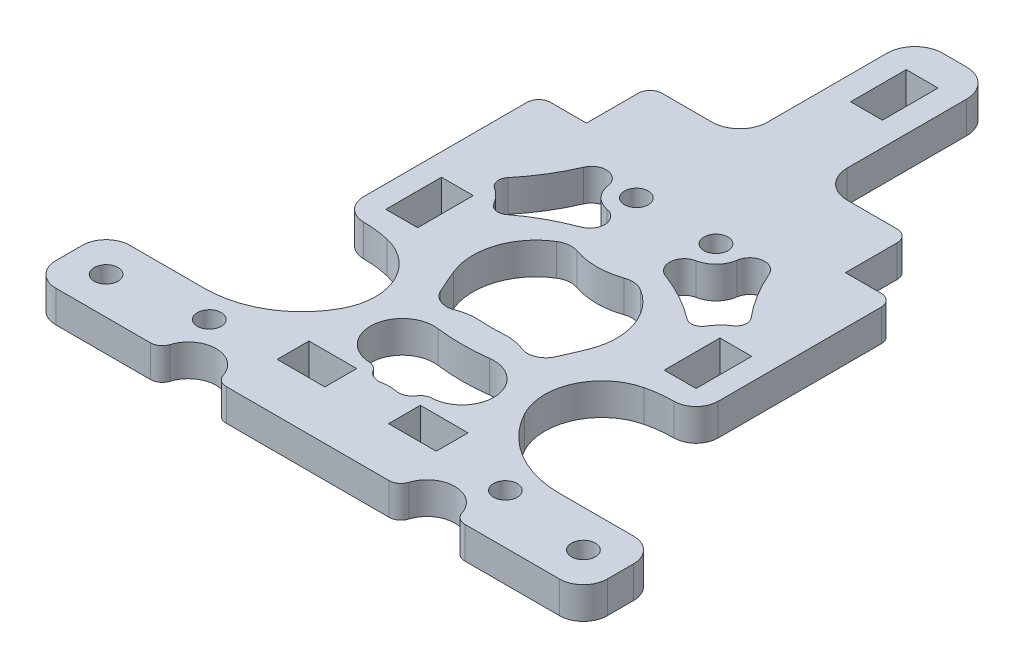
SolidWorks part; units mm, degrees
ref_plane "Plan de face" through (0, 0, 0) normal (0, 0, 1) x (1, 0, 0)
ref_plane "Plan de dessus" through (0, 0, 0) normal (0, 1, 0) x (1, 0, 0)
ref_plane "Plan de droite" through (0, 0, 0) normal (1, 0, 0) x (0, 0, -1)
sketch "Esquisse1" plane through (0, 0, 0) normal (0, 1, 0) x (1, 0, 0)
  line L0 (0, -203.16) -> (0, 154.3311) construction
  line L1 (-20.28, 5) -> (-22.28, 5)
  line L2 (-20.28, 5) -> (-16.28, 5)
  line L3 (-5, 35) -> (-5, 13)
  line L4 (-22.28, 5) -> (-22.28, -122.6773) construction
  line L5 (-22.28, -122.6773) -> (0.6971, -122.6773) construction
  line L6 (2, 30.92) -> (-2, 30.92)
  line L7 (-2, 30.92) -> (-2, 23.92)
  line L8 (-2, 23.92) -> (2, 23.92)
  line L9 (-18.1387, -5) -> (23.5208, -5) construction
  line L10 (-19.5, -10) -> (-15.5, -10)
  line L11 (-19.5, -10) -> (-19.5, -17)
  line L12 (-19.5, -17) -> (-15.5, -17)
  line L13 (-15.5, -10) -> (-15.5, -17)
  line L14 (-10, -36.16) -> (-4, -36.16)
  line L15 (-10, -36.16) -> (-10, -40.16)
  line L16 (-10, -40.16) -> (-4, -40.16)
  line L17 (-4, -36.16) -> (-4, -40.16)
  line L18 (-5, 35) -> (5, 35)
  line L19 (-22.28, 5) -> (-22.28, -37)
  line L21 (-5, 13) -> (-16.28, 13)
  line L22 (-16.28, 13) -> (-16.28, 5)
  line L23 (18.1387, -5) -> (-23.5208, -5) construction
  line L24 (16.28, 13) -> (16.28, 5)
  line L25 (5, 13) -> (16.28, 13)
  line L26 (22.28, 5) -> (22.28, -37)
  line L27 (4, -36.16) -> (4, -40.16)
  line L28 (10, -40.16) -> (4, -40.16)
  line L29 (10, -36.16) -> (10, -40.16)
  line L30 (10, -36.16) -> (4, -36.16)
  line L31 (15.5, -10) -> (15.5, -17)
  line L32 (19.5, -17) -> (15.5, -17)
  line L33 (19.5, -10) -> (19.5, -17)
  line L34 (19.5, -10) -> (15.5, -10)
  line L35 (2, 30.92) -> (2, 23.92)
  line L36 (5, 35) -> (5, 13)
  line L37 (20.28, 5) -> (16.28, 5)
  line L38 (20.28, 5) -> (22.28, 5)
  line L39 (-22.28, -37) -> (-34.66, -37)
  line L40 (-34.66, -37) -> (-34.66, -46.32)
  line L44 (-34.66, -46.32) -> (34.66, -46.32)
  line L45 (-30, -41.66) -> (-34.66, -37) construction
  line L46 (-30, -41.66) -> (-34.66, -46.32) construction
  line L47 (22.28, -37) -> (34.66, -37)
  line L48 (34.66, -37) -> (34.66, -46.32)
  line L49 (30, -41.66) -> (34.66, -37) construction
  line L50 (30, -41.66) -> (34.66, -46.32) construction
  circle A0 centre (-5, 0) radius 1.5
  circle A1 centre (5, 0) radius 1.5
  circle A2 centre (-30, -41.66) radius 1.5
  circle A3 centre (30, -41.66) radius 1.5
  point P38 (0, -40.4225)
  point P40 (0, 35)
  point P49 (0, 23.92)
  point P50 (0, 30.92)
  point P60 (0, -46.32)
  dimension "D2" = 3
  dimension "D22" = 3
  dimension "D1" = 10
  dimension "D3" = 15.28
  dimension "D4" = 4
  dimension "D5" = 5
  dimension "D6" = 6
  dimension "D7" = 7
  dimension "D8" = 2
  dimension "D9" = 26.16
  dimension "D10" = 4
  dimension "D11" = 8
  dimension "D12" = 13.5
  dimension "D13" = 40.92
  dimension "D14" = 5
  dimension "D15" = 40
  dimension "D16" = 6
  dimension "D17" = 5
  dimension "D18" = 18
  dimension "D19" = 20
  dimension "D20" = 1.5
  dimension "D21" = 42
extrude "Boss.-Extru.1" add sketch "Esquisse1" along normal blind 4
sketch "Esquisse2" plane through (0, 4, 0) normal (0, 1, 0) x (1, 0, 0)
  line L0 (0, 18.1178) -> (0, -30.7499) construction
  line L1 (-15.5, -10) -> (-17.1999, -11.6189) construction
  line L3 (-5.938, -4.9112) -> (-5, 0) construction
  line L4 (-5, 0) -> (-9.9511, -0.6975) construction
  line L5 (-14.2621, -6.7262) -> (-15.5, -10) construction
  line L6 (-15.5, -10) -> (-12.1698, -8.9231) construction
  line L7 (15.5, -10) -> (12.1698, -8.9231) construction
  line L8 (14.2621, -6.7262) -> (15.5, -10) construction
  line L9 (5, 0) -> (9.9511, -0.6975) construction
  line L10 (5.938, -4.9112) -> (5, 0) construction
  line L11 (15.5, -10) -> (17.1999, -11.6189) construction
  arc A0 (-14.9975, -7.8435) -> (-13.3216, -9.6032) centre (-17.9572, -12.3402) cw
  arc A1 (-13.3216, -9.6032) -> (-11.3615, -9.9889) centre (-12.1698, -8.9231) ccw
  arc A2 (-11.3615, -9.9889) -> (-5.29, -6.6501) centre (3.022, -28.9549) cw
  arc A8 (-11.6563, 0.0345) -> (-15.2872, -5.867) centre (-33.5294, 9.4241) cw
  arc A9 (-15.2872, -5.867) -> (-14.9975, -7.8435) centre (-14.2621, -6.7262) ccw
  arc A10 (-11.6563, 0.0345) -> (-8.1136, -0.4386) centre (-9.9511, -0.6975) cw
  arc A11 (-8.1136, -0.4386) -> (-5.5899, -3.0885) centre (-5, 0) ccw
  arc A12 (-5.5899, -3.0885) -> (-5.29, -6.6501) centre (-5.938, -4.9112) cw
  circle A13 centre (-5, 0) radius 1.5 construction
  arc A14 (5.5899, -3.0885) -> (5.29, -6.6501) centre (5.938, -4.9112) ccw
  arc A15 (8.1136, -0.4386) -> (5.5899, -3.0885) centre (5, 0) cw
  arc A16 (11.6563, 0.0345) -> (8.1136, -0.4386) centre (9.9511, -0.6975) ccw
  arc A17 (15.2872, -5.867) -> (14.9975, -7.8435) centre (14.2621, -6.7262) cw
  arc A18 (11.6563, 0.0345) -> (15.2872, -5.867) centre (33.5294, 9.4241) ccw
  arc A19 (11.3615, -9.9889) -> (5.29, -6.6501) centre (-3.022, -28.9549) ccw
  arc A20 (13.3216, -9.6032) -> (11.3615, -9.9889) centre (12.1698, -8.9231) cw
  arc A21 (14.9975, -7.8435) -> (13.3216, -9.6032) centre (17.9572, -12.3402) ccw
  dimension "D1" = 5
  dimension "D2" = 3.5
extrude "Enlèv. mat.-Extru.1" cut sketch "Esquisse2" against normal up to next
sketch "Esquisse3" plane through (0, 4, 0) normal (0, 1, 0) x (1, 0, 0)
  line L0 (0, -74.8018) -> (0, 54.5736) construction
  line L1 (-4, -36.16) -> (-5.4516, -38.6743) construction
  line L2 (4, -36.16) -> (5.4516, -38.6743) construction
  line L3 (3.9346, -34.6614) -> (4, -36.16) construction
  line L4 (4, -36.16) -> (2.7349, -35.3541) construction
  line L5 (10, -36.16) -> (4, -36.16) construction
  arc A0 (-3.9346, -34.6614) -> (-2.7349, -35.3541) centre (-4, -36.16) cw
  arc A1 (2.7349, -35.3541) -> (3.9346, -34.6614) centre (4, -36.16) cw
  arc A2 (-2.7349, -35.3541) -> (-0.9018, -36.1339) centre (-1.25, -34.4081) ccw
  arc A3 (2.7349, -35.3541) -> (0.9018, -36.1339) centre (1.25, -34.4081) cw
  arc A4 (0.9018, -36.1339) -> (-0.9018, -36.1339) centre (0, -40.6041) ccw
  arc A5 (-3.9346, -34.6614) -> (-3.25, -26.6979) centre (-3.7601, -30.6652) cw
  arc A6 (3.9346, -34.6614) -> (3.25, -26.6979) centre (3.7601, -30.6652) ccw
  arc A7 (3.25, -26.6979) -> (-3.25, -26.6979) centre (0, -1.4204) cw
  dimension "D5" = 4
  dimension "D1" = 1.5
  dimension "D2" = 2.5
  dimension "D3" = 55
  dimension "D4" = 60
  dimension "D6" = 6.5
extrude "Enlèv. mat.-Extru.2" cut sketch "Esquisse3" against normal up to next
sketch "Esquisse4" plane through (0, 4, 0) normal (0, 1, 0) x (1, 0, 0)
  line L0 (0, 0) -> (0, -34.64) construction
  arc A0 (-1.505, -23.1854) -> (1.505, -23.1854) centre (0, -1.4204) ccw
  arc A1 (-3.25, -26.6979) -> (3.25, -26.6979) centre (0, -1.4204) ccw construction
  arc A2 (-1.505, -23.1854) -> (-4.2382, -23.6133) centre (-1.9339, -29.3882) ccw
  arc A3 (-4.2382, -23.6133) -> (-7.1847, -22.4339) centre (-5.0915, -21.4748) cw
  arc A4 (-7.1847, -22.4339) -> (-8.4526, -19.5068) centre (62.3097, 9.4075) cw
  arc A5 (-8.4526, -19.5068) -> (-5.2684, -9.7546) centre (-1.1124, -16.5075) cw
  arc A6 (-5.2684, -9.7546) -> (-2.9573, -9.5004) centre (-3.8445, -12.0683) cw
  arc A7 (-2.9573, -9.5004) -> (2.9573, -9.5004) centre (0, -0.9399) ccw
  arc A8 (2.9573, -9.5004) -> (5.2684, -9.7546) centre (3.8445, -12.0683) cw
  arc A10 (7.1847, -22.4339) -> (4.2382, -23.6133) centre (5.0915, -21.4748) cw
  arc A11 (4.2382, -23.6133) -> (1.505, -23.1854) centre (1.9339, -29.3882) ccw
  arc A12 (5.2684, -9.7546) -> (8.4526, -19.5068) centre (1.1124, -16.5075) cw
  arc A13 (8.4526, -19.5068) -> (7.1847, -22.4339) centre (-62.3097, 9.4075) cw
extrude "Enlèv. mat.-Extru.3" cut sketch "Esquisse4" against normal up to next
fillet "Congé1" radius 3.5 2 edges at (-5, 2, -35) (5, 2, -35)
fillet "Congé2" radius 3.5 2 edges at (5, 2, -13) (-5, 2, -13)
fillet "Congé3" radius 1.5 4 edges at (22.28, 2, -5) (-22.28, 2, -5) (-16.28, 2, -13) (16.28, 2, -13)
sketch "Esquisse7" plane through (0, 4, 0) normal (0, 1, 0) x (1, 0, 0)
  line L0 (-22.28, 3.5) -> (-22.28, -37) construction
  line L1 (-22.28, -37) -> (-34.66, -37) construction
  line L2 (-22.28, -17) -> (-22.28, -37)
  arc A0 (-22.28, -17) -> (-19.5, -19.78) centre (-19.5, -17) ccw
  arc A1 (-19.5, -19.78) -> (-16.1469, -20.1748) centre (-19.5, -34.2169) cw
  arc A2 (-16.1469, -20.1748) -> (-11.4957, -30.5617) centre (-17.814, -27.1561) cw
  arc A3 (-11.4957, -30.5617) -> (-22.28, -37) centre (-22.28, -24.7489) cw
extrude "Enlèv. mat.-Extru.4" cut sketch "Esquisse7" against normal up to next
mirror "Symétrie1" about plane through (0, 0, 0) normal (1, 0, 0) of "Enlèv. mat.-Extru.4"
fillet "Congé4" radius 3 2 edges at (-34.66, 2, 37) (-34.66, 2, 46.32)
fillet "Congé5" radius 3 2 edges at (34.66, 2, 37) (34.66, 2, 46.32)
sketch "Esquisse8" plane through (0, 4, 0) normal (0, 1, 0) x (1, 0, 0)
  line L0 (0, -14.2403) -> (0, -4.5022) construction
  line L1 (-31.66, -46.32) -> (31.66, -46.32) construction
  circle A0 centre (-15, -46.32) radius 3.5
  circle A1 centre (15, -46.32) radius 3.5
  dimension "D2" = 7
  dimension "D1" = 30
extrude "Enlèv. mat.-Extru.5" cut sketch "Esquisse8" against normal up to next
fillet "Congé6" radius 1.5 4 edges at (11.5, 2, 46.32) (18.5, 2, 46.32) (-18.5, 2, 46.32) (-11.5, 2, 46.32)
sketch "Esquisse9" plane through (0, 4, 0) normal (0, 1, 0) x (1, 0, 0)
  line L0 (-16.7519, -43.29) -> (-18.6094, -40.0776) construction
  line L1 (-20.4669, -36.8651) -> (-18.6094, -40.0776) construction
  circle A0 centre (-18.6094, -40.0776) radius 1.5
  circle A1 centre (-30, -41.66) radius 1.5 construction
  arc A2 (-11.6612, -45.27) -> (-18.3388, -45.27) centre (-15, -46.32) ccw construction
  arc A3 (-22.28, -37) -> (-11.4957, -30.5617) centre (-22.28, -24.7489) ccw construction
  circle A4 centre (-15, -46.32) radius 2.2908 construction
  point P5 (-20.1079, -36.8059)
  dimension "D2" = 3
  dimension "D1" = 11.5
extrude "Enlèv. mat.-Extru.6" cut sketch "Esquisse9" against normal up to next
mirror "Symétrie2" about plane through (0, 0, 0) normal (1, 0, 0) of "Enlèv. mat.-Extru.6"
